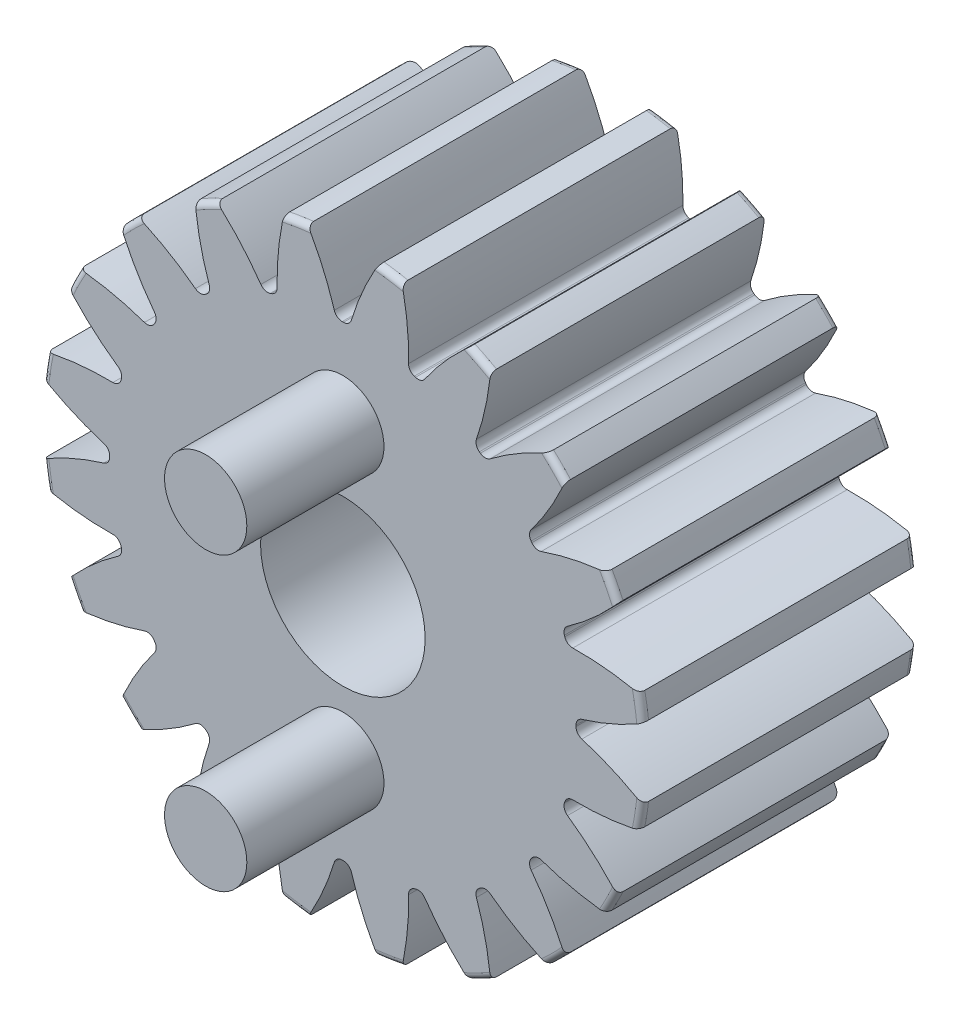
SolidWorks part; units mm, degrees
ref_plane "Front Plane" through (0, 0, 0) normal (0, 0, 1) x (1, 0, 0)
ref_plane "Top Plane" through (0, 0, 0) normal (0, 1, 0) x (1, 0, 0)
ref_plane "Right Plane" through (0, 0, 0) normal (1, 0, 0) x (0, 0, -1)
sketch "Sketch1" plane through (0, 0, 0) normal (0, 0, 1) x (1, 0, 0)
  line L0 (-254, 0) -> (254, 0) construction
  circle A0 centre (0, 0) radius 13.97 construction
  circle A1 centre (0, 0) radius 12.7 construction
  circle A2 centre (0, 0) radius 10.795 construction
  circle A3 centre (0, 0) radius 10.8331 construction
  circle A4 centre (0, 0) radius 6.35 construction
  circle A5 centre (0, 0) radius 10.3187 construction
  dimension "D2" = 1.27
  dimension "D3" = 3.175
  dimension "D1" = 3.175
sketch "Sketch2" plane through (0, 0, 0) normal (1, 0, 0) x (0, 0, -1)
  line L0 (0, 0) -> (-12.7, 0) construction
  line L1 (-12.7, 0) -> (-23.8252, 0) construction
  dimension "Overall Width" = 23.8252
  dimension "Face Width" = 12.7
sketch "Sketch4" plane through (0, 0, 0) normal (1, 0, 0) x (0, 0, -1)
  line L0 (-23.8252, 6.35) -> (-23.8252, 10.8331)
  line L1 (-23.8252, 10.8331) -> (-12.7, 10.8331)
  line L2 (-12.7, 10.8331) -> (-12.7, 13.97)
  line L3 (-12.7, 13.97) -> (0, 13.97)
  line L4 (0, 13.97) -> (0, 6.35)
  line L5 (-12.7, 10.8331) -> (-12.7, 0) construction
  line L6 (0, 13.97) -> (0, -13.97) construction
  line L7 (-12.7, 10.8331) -> (0, 10.8331) construction
  line L12 (-23.8252, 6.35) -> (0, 6.35)
revolve "Revolve1" add sketch "Sketch4" angle 360 about L1
fillet "Fillet2" radius 0.2794 4 edges at (0, 10.8331, 23.8252) (0, 10.8331, 12.7) (0, 13.97, 12.7) (0, 13.97, 0)
sketch "Sketch7" plane through (0, 0, 12.7) normal (0, 0, 1) x (1, 0, 0)
  line L0 (0, 0) -> (0, 13.97) construction
  line L1 (0.9964, 12.6609) -> (1.5536, 13.8833) construction
  line L3 (2.1854, 13.798) -> (1.9867, 12.5436) construction
  line L4 (1.9867, 12.5436) -> (1.6887, 10.6621) construction
  line L5 (0, 0) -> (1.6887, 10.6621) construction
  line L6 (0.9964, 12.6609) -> (0, 0) construction
  line L7 (0.9964, 12.6609) -> (1.0961, 13.9269) construction
  line L8 (0.9964, 12.6609) -> (0, 0) construction
  circle A0 centre (0, 0) radius 13.97 construction
  arc A1 (-0.0294, 10.795) -> (0.0294, 10.795) centre (0, 0) cw
  circle A2 centre (0, 0) radius 10.795 construction
  arc A3 (-0.9964, 12.6609) -> (0.9964, 12.6609) centre (0, 0) cw construction
  circle A4 centre (0, 0) radius 12.7 construction
  arc A5 (2.7366, 13.6993) -> (1.6307, 13.8745) centre (0, 0) ccw construction
  arc A6 (0.9964, 12.6609) -> (2.9648, 12.3491) centre (0, 0) cw construction
  arc A7 (-1.6307, 13.8745) -> (1.6307, 13.8745) centre (0, 0) cw
  arc A8 (0.3952, 11.0658) -> (1.6307, 13.8745) centre (12.5529, 7.3942) cw
  arc A9 (-0.3952, 11.0658) -> (-1.6307, 13.8745) centre (-12.5529, 7.3942) ccw
  arc A10 (-0.0294, 10.795) -> (-0.3952, 11.0658) centre (-0.0305, 11.176) cw
  arc A11 (0.0294, 10.795) -> (0.3952, 11.0658) centre (0.0305, 11.176) ccw
  point P26 (-0.3154, 10.7904)
  point P29 (0.3154, 10.7904)
  dimension "D4" = 0.381
  dimension "D5" = 12.7
  dimension "D3" = 20
  dimension "D1" = 3.9898
  dimension "D2" = 1.9949
extrude "Cut-Extrude2" cut sketch "Sketch7" against normal through all
pattern_circular "CirPattern1" count 20 over 360 about axis through (0, 0, 0) along (0, 0, 1) of "Cut-Extrude2"
sketch "Sketch9" [suppressed] plane through (0, 0, 0) normal (0, 0, 1) x (1, 0, 0)
  circle A0 centre (0, 0) radius 10.3187 construction
  circle A1 centre (0, 0) radius 10.3187
sketch "Sketch11" plane through (0, 0, 23.8252) normal (0, 0, 1) x (1, 0, 0)
  circle A0 centre (0, 0) radius 11.43
  dimension "D1" = 22.86
extrude "Cut-Extrude3" cut sketch "Sketch11" against normal blind 11.1252
sketch "Sketch13" plane through (0, 0, 12.7) normal (0, 0, 1) x (1, 0, 0)
  circle A0 centre (0, 0) radius 6.35
  dimension "D1" = 12.7
extrude "Boss-Extrude1" add sketch "Sketch13" against normal blind 12.7
sketch "Sketch15" plane through (0, 0, 0) normal (0, 0, -1) x (-1, 0, 0)
  circle A0 centre (0, 0) radius 3.81
  dimension "D1" = 7.62
extrude "Cut-Extrude4" cut sketch "Sketch15" against normal through all
sketch "Sketch16" plane through (0, 0, 12.7) normal (0, 0, 1) x (1, 0, 0)
  line L0 (0, -6.7469) -> (0, 6.7469) construction
  circle A0 centre (0, -6.7469) radius 1.905
  circle A1 centre (0, 6.7469) radius 1.905
  dimension "D1" = 3.81
  dimension "D2" = 13.4937
extrude "Boss-Extrude2" add sketch "Sketch16" along normal blind 6.35 contours A1 | A0
equation "\"D1@Sketch1\"=2.5*(\"Pitch Dia.@Sketch1\"/\"Number of Teeth@Sketch1\")"
equation "\"D1@CirPattern1\"=\"Number of Teeth@Sketch1\""
equation "\"D1@Fillet2\"=\"OD@Sketch1\"*.01"
equation "\"D1@Sketch7\"=3.14159*(\"Pitch Dia.@Sketch1\"/\"Number of Teeth@Sketch1\")"
equation "\"D2@Sketch7\"=\"D1@Sketch7\"/2"
equation "\"D4@Sketch7\"=\"D1@Sketch7\"*.0955"
equation "\"D5@Sketch7\"=\"Pitch Dia.@Sketch1\"/2"
